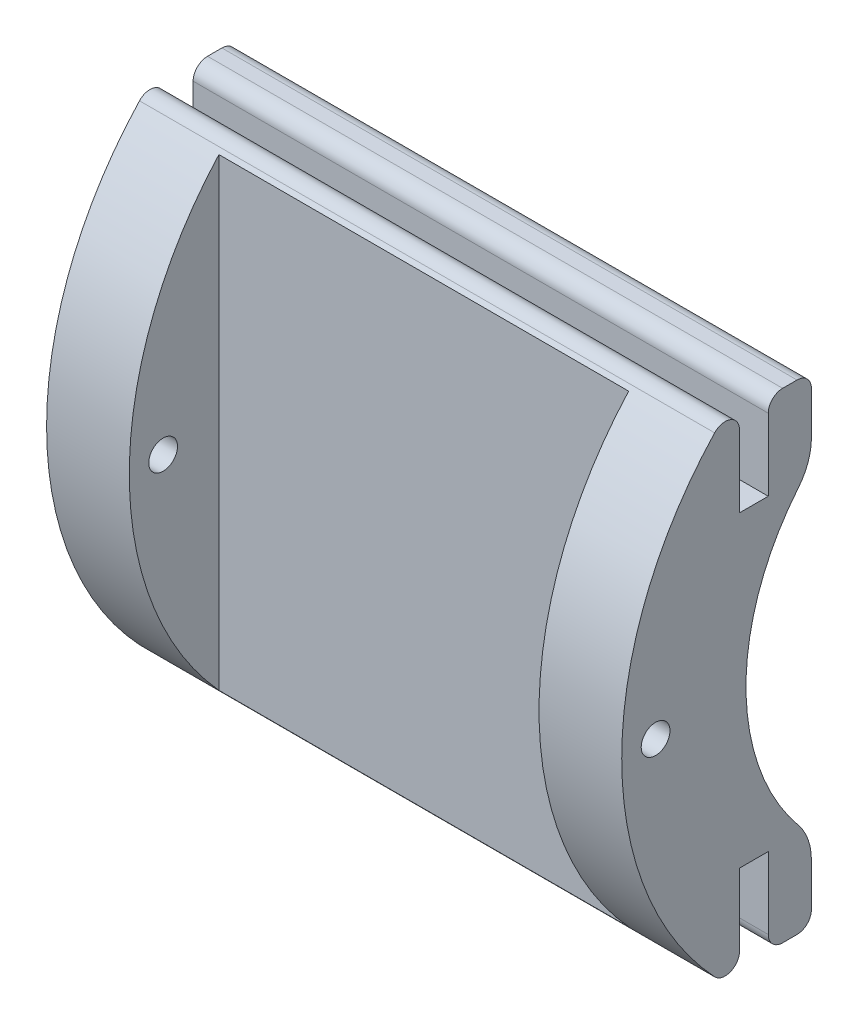
SolidWorks part; units mm, degrees
ref_plane "Front Plane" through (0, 0, 0) normal (1, 0, 0) x (0, 1, 0)
ref_plane "Top Plane" through (0, 0, 0) normal (0, 0, 1) x (0, 1, 0)
ref_plane "Right Plane" through (0, 0, 0) normal (0, 1, 0) x (-1, 0, 0)
sketch "Sketch2" plane through (0, 0, 0) normal (1, 0, 0) x (0, 1, 0)
  line L0 (-63.5, -22.7488) -> (-78.5, -22.7488)
  line L1 (-83.5, -17.7488) -> (-83.5, -12.7488)
  line L2 (-78.5, -7.7488) -> (-53.5, -7.7488)
  line L3 (-53.5, -7.7488) -> (-53.5, 2.2512)
  line L4 (-53.5, 2.2512) -> (-78.5, 2.2512)
  line L5 (63.5, -22.7488) -> (78.5, -22.7488)
  line L6 (83.5, -17.7488) -> (83.5, -12.7488)
  line L7 (78.5, -7.7488) -> (53.5, -7.7488)
  line L8 (53.5, -7.7488) -> (53.5, 2.2512)
  line L9 (53.5, 2.2512) -> (78.5, 2.2512)
  arc A0 (-50.8, -18.199) -> (50.8, -18.199) centre (0, -80) cw
  arc A1 (-81.913, 10.9051) -> (81.913, 10.9051) centre (0, -76.789) cw
  circle A2 centre (0, 31.438) radius 5
  arc A4 (50.8, -18.199) -> (63.5, -22.7488) centre (63.5, -2.7488) ccw
  arc A5 (-50.8, -18.199) -> (-63.5, -22.7488) centre (-63.5, -2.7488) cw
  arc A6 (78.5, -22.7488) -> (83.5, -17.7488) centre (78.5, -17.7488) ccw
  arc A7 (83.5, -12.7488) -> (78.5, -7.7488) centre (78.5, -12.7488) ccw
  arc A8 (78.5, 2.2512) -> (81.913, 10.9051) centre (78.5, 7.2512) ccw
  arc A9 (-78.5, 2.2512) -> (-81.913, 10.9051) centre (-78.5, 7.2512) cw
  arc A10 (-78.5, -22.7488) -> (-83.5, -17.7488) centre (-78.5, -17.7488) cw
  arc A11 (-83.5, -12.7488) -> (-78.5, -7.7488) centre (-78.5, -12.7488) cw
  point P17 (0, 0)
  point P20 (0, 0)
  point P30 (0, 43.211)
  point P39 (55.8775, -22.7488)
  point P42 (-55.8775, -22.7488)
  dimension "D1" = 80
  dimension "D2" = 120
  dimension "D3" = 10
  dimension "D4" = 20
  dimension "D5" = 5
  dimension "D11" = 101.6
  dimension "D6" = 15
  dimension "D7" = 15
  dimension "D8" = 10
  dimension "D9" = 25
extrude "Boss-Extrude1" add sketch "Sketch2" along normal blind 200
sketch "Sketch3" plane through (0, 0, 0) normal (0, 1, 0) x (-1, 0, 0)
  line L0 (-200, 36.438) -> (-200, 26.438) construction
  line L1 (-200, 36.438) -> (-200, 26.438)
  line L2 (-1200, 31.438) -> (48800, 31.438) construction
  line L3 (-100, -1065.2015) -> (-100, 48934.7985) construction
  line L4 (-200, -22.7488) -> (0, -22.7488) construction
  line L6 (-28.7528, 12.0499) -> (-171.2472, 12.0499)
  line L7 (-28.7528, 12.0499) -> (-28.7528, 50.8261)
  line L8 (-28.7528, 50.8261) -> (-171.2472, 50.8261)
  line L9 (-171.2472, 12.0499) -> (-171.2472, 50.8261)
  line L10 (-28.7528, 12.0499) -> (-171.2472, 50.8261) construction
  line L11 (-28.7528, 50.8261) -> (-171.2472, 12.0499) construction
  point P5 (-200, 31.438)
  point P6 (-100, 31.438)
  point P10 (-100, -22.7488)
extrude "Cut-Extrude1" cut sketch "Sketch3" against normal through all both and the other way through all contours L7 L8 L9 L6
